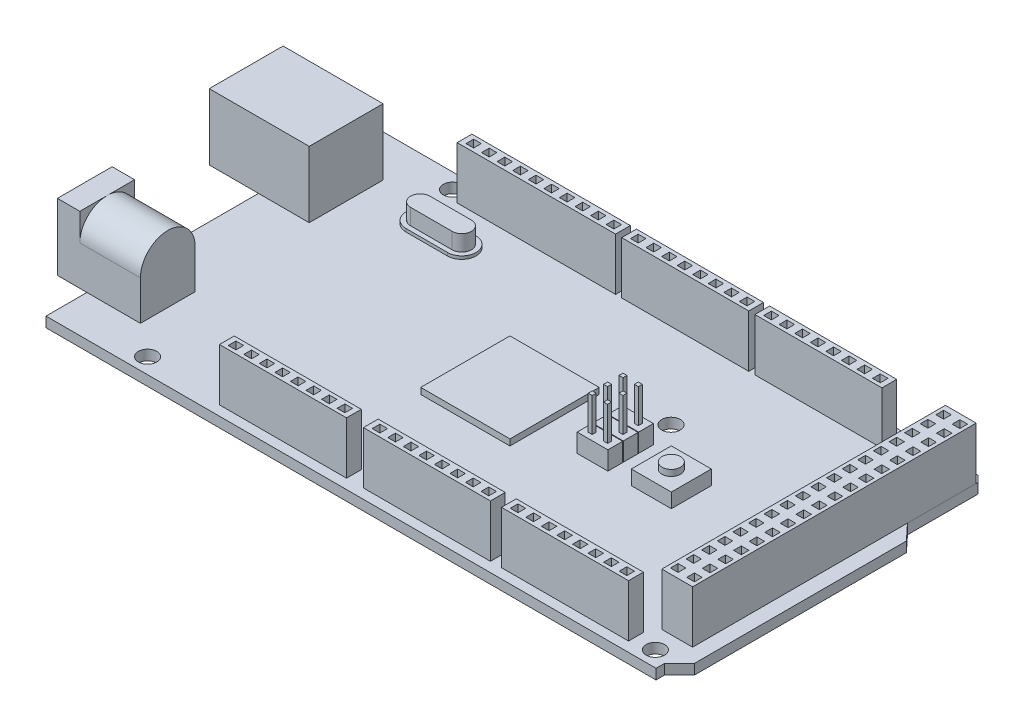
SolidWorks part; units mm, degrees
ref_plane "Front Plane" through (0, 0, 0) normal (0, 0, 1) x (1, 0, 0)
ref_plane "Top Plane" through (0, 0, 0) normal (0, 1, 0) x (1, 0, 0)
ref_plane "Right Plane" through (0, 0, 0) normal (1, 0, 0) x (0, 0, -1)
sketch "Sketch3" plane through (0, 0, 0) normal (0, 1, 0) x (1, 0, 0)
  line L0 (35.6106, 186.2409) -> (435.6106, 186.2409) construction
  line L1 (50.8, -26.67) -> (-50.8, -26.67)
  line L2 (50.8, -26.67) -> (50.8, 26.67)
  line L3 (50.8, 26.67) -> (-50.8, 26.67)
  line L4 (-50.8, -26.67) -> (-50.8, 26.67)
  line L5 (0, 26.67) -> (0, -26.67) construction
  line L6 (50.8, 0) -> (-50.8, 0) construction
  line L7 (47.3673, 26.67) -> (48.3673, 25.67)
  line L8 (48.3673, 25.67) -> (48.3673, 14.2013)
  line L9 (48.3673, 14.2013) -> (50.8, 11.5986)
  line L10 (50.8, -22.8744) -> (48.3673, -25.3071)
  line L11 (48.3673, -25.3071) -> (48.3673, -26.67)
  circle A0 centre (-36.83, -24.13) radius 1.5
  circle A1 centre (-35.56, 24.17) radius 1.5
  circle A2 centre (39.37, 24.17) radius 1.5
  circle A3 centre (45.72, -24.13) radius 1.5
  circle A4 centre (15.24, -19.05) radius 1.5
  circle A5 centre (15.3, 8.83) radius 1.5
  point P0 (0, 0)
  dimension "D4" = 3
  dimension "D7" = 3
  dimension "D1" = 101.6
  dimension "D2" = 53.34
  dimension "D3" = 15.24
  dimension "D5" = 2.5
  dimension "D6" = 2.54
  dimension "D8" = 13.97
  dimension "D9" = 90.17
  dimension "D10" = 96.52
  dimension "D11" = 66.04
  dimension "D12" = 7.62
  dimension "D13" = 1
  dimension "D14" = 1
  dimension "D15" = 35.5
  dimension "D16" = 35.5
extrude "Boss-Extrude1" add sketch "Sketch3" along normal blind 1.65 contours L11 L10 L2 L9 L8 L7 L3 L4 L1 A4 A3 A2 A1 A0
sketch "Sketch4" plane through (0, 1.65, 0) normal (0, 1, 0) x (1, 0, 0)
  line L0 (-50.8, -26.67) -> (-50.8, 26.67) construction
  line L1 (-42.55, 19.87) -> (-58.8, 19.87)
  line L2 (-42.55, 19.87) -> (-42.55, 7.87)
  line L3 (-42.55, 7.87) -> (-58.8, 7.87)
  line L4 (-58.8, 19.87) -> (-58.8, 7.87)
  line L5 (-50.675, 7.87) -> (-50.675, 19.87) construction
  line L6 (-42.55, 13.87) -> (-58.8, 13.87) construction
  line L13 (47.3673, 26.67) -> (-50.8, 26.67) construction
  point P60 (-50.675, 13.87)
  dimension "D1" = 16.25
  dimension "D2" = 12
  dimension "D3" = 8
  dimension "D4" = 6.8
extrude "Boss-Extrude2" add sketch "Sketch4" along normal blind 10.75 separate body
sketch "Sketch5" plane through (0, 1.65, 0) normal (0, 1, 0) x (1, 0, 0)
  line L0 (-50.8, -26.67) -> (-50.8, 26.67) construction
  line L1 (-42.1, -11.12) -> (-55.6, -11.12)
  line L2 (-42.1, -11.12) -> (-42.1, -20.02)
  line L3 (-42.1, -20.02) -> (-55.6, -20.02)
  line L4 (-55.6, -11.12) -> (-55.6, -20.02)
  line L5 (-48.85, -20.02) -> (-48.85, -11.12) construction
  line L6 (-42.1, -15.57) -> (-55.6, -15.57) construction
  line L7 (48.3673, -26.67) -> (-50.8, -26.67) construction
  point P64 (-48.85, -15.57)
  dimension "D1" = 13.5
  dimension "D2" = 8.9
  dimension "D3" = 4.8
  dimension "D4" = 6.65
extrude "Boss-Extrude3" add sketch "Sketch5" along normal blind 10.85 separate body
sketch "Sketch6" plane through (-42.1, 0, 0) normal (1, 0, 0) x (0, 0, -1)
  line L0 (-20.02, 12.5) -> (-20.02, 1.65) construction
  line L1 (-11.12, 12.5) -> (-11.12, 1.65) construction
  line L2 (-20.02, 12.5) -> (-11.12, 12.5) construction
  line L3 (-20.02, 8.05) -> (-20.02, 13.329)
  line L4 (-20.02, 13.329) -> (-11.12, 13.329)
  line L5 (-11.12, 13.329) -> (-11.12, 8.05)
  arc A0 (-20.02, 8.05) -> (-11.12, 8.05) centre (-15.57, 8.05) cw
extrude "Cut-Extrude1" cut sketch "Sketch6" against normal offset from surface (9.85 mm away) 3.65 up to face at (-55.6, 7.075, 15.57)
sketch "Sketch7" plane through (-58.8, 0, 0) normal (-1, 0, 0) x (0, 0, 1)
  line L0 (-7.87, 12.4) -> (-7.87, 1.65) construction
  line L1 (-18.22, 2.95) -> (-9.52, 2.95)
  line L2 (-18.22, 2.95) -> (-18.22, 9.1)
  line L3 (-16.22, 11.1) -> (-11.52, 11.1)
  line L4 (-9.52, 2.95) -> (-9.52, 9.1)
  line L5 (-13.87, 11.1) -> (-13.87, 2.95) construction
  line L6 (-18.22, 7.025) -> (-9.52, 7.025) construction
  line L7 (-19.87, 12.4) -> (-7.87, 12.4) construction
  line L8 (-18.22, 9.1) -> (-16.22, 11.1)
  line L9 (-11.02, 5.45) -> (-16.72, 5.45)
  line L10 (-11.02, 5.45) -> (-11.02, 8.6)
  line L11 (-11.02, 8.6) -> (-16.72, 8.6)
  line L12 (-16.72, 5.45) -> (-16.72, 8.6)
  line L13 (-13.87, 8.6) -> (-13.87, 5.45) construction
  line L14 (-11.02, 7.025) -> (-16.72, 7.025) construction
  line L15 (-11.52, 11.1) -> (-9.52, 9.1)
  point P0 (-13.87, 7.025)
  point P1 (-9.52, 11.1)
  point P3 (-18.22, 11.1)
  point P6 (-7.87, 7.025)
  point P9 (-13.87, 12.4)
  point P10 (-13.87, 7.025)
  dimension "D1" = 1.65
  dimension "D2" = 1.3
  dimension "D3" = 5.7
  dimension "D4" = 3.15
extrude "Cut-Extrude2" cut sketch "Sketch7" against normal blind 13
sketch "Sketch8" plane through (-55.6, 0, 0) normal (-1, 0, 0) x (0, 0, 1)
  circle A0 centre (15.57, 8.05) radius 3
  circle A1 centre (15.57, 8.05) radius 0.75
  dimension "D1" = 6
  dimension "D2" = 1.5
extrude "Cut-Extrude3" cut sketch "Sketch8" against normal blind 10
fillet "Fillet1" radius 0.75 1 edges at (-55.6, 8.05, 16.32)
sketch "Sketch9" plane through (0, 1.65, 0) normal (0, 1, 0) x (1, 0, 0)
  line L0 (48.3673, 25.67) -> (48.3673, 14.2013) construction
  line L1 (48.3673, 25.37) -> (43.3673, 25.37)
  line L2 (48.3673, 25.37) -> (48.3673, -20.73)
  line L3 (48.3673, -20.73) -> (43.3673, -20.73)
  line L4 (43.3673, 25.37) -> (43.3673, -20.73)
  line L5 (45.8673, -20.73) -> (45.8673, 25.37) construction
  line L6 (48.3673, 2.32) -> (43.3673, 2.32) construction
  line L7 (47.3673, 26.67) -> (-50.8, 26.67) construction
  line L8 (45.1673, -18.63) -> (43.9173, -18.63)
  line L9 (46.5673, -19.88) -> (47.8173, -19.88)
  line L10 (46.5673, -19.88) -> (46.5673, -18.63)
  line L11 (46.5673, -18.63) -> (47.8173, -18.63)
  line L12 (47.8173, -19.88) -> (47.8173, -18.63)
  line L13 (47.1923, -18.63) -> (47.1923, -19.88) construction
  line L14 (46.5673, -19.255) -> (47.8173, -19.255) construction
  line L15 (43.9173, -19.88) -> (43.9173, -18.63)
  line L16 (45.1673, -19.88) -> (43.9173, -19.88)
  line L17 (45.1673, -19.88) -> (45.1673, -18.63)
  line L18 (45.1673, -19.255) -> (43.9173, -19.255) construction
  line L19 (44.5423, -18.63) -> (44.5423, -19.88) construction
  line L20 (45.1673, -16.0918) -> (43.9173, -16.0918)
  line L21 (46.5673, -17.3418) -> (47.8173, -17.3418)
  line L22 (46.5673, -17.3418) -> (46.5673, -16.0918)
  line L23 (46.5673, -16.0918) -> (47.8173, -16.0918)
  line L24 (47.8173, -17.3418) -> (47.8173, -16.0918)
  line L25 (43.9173, -17.3418) -> (43.9173, -16.0918)
  line L26 (45.1673, -17.3418) -> (43.9173, -17.3418)
  line L27 (45.1673, -17.3418) -> (45.1673, -16.0918)
  line L28 (47.1923, -16.0918) -> (47.1923, -17.3418) construction
  line L29 (46.5673, -16.7168) -> (47.8173, -16.7168) construction
  line L30 (45.1673, -16.7168) -> (43.9173, -16.7168) construction
  line L31 (44.5423, -16.0918) -> (44.5423, -17.3418) construction
  line L32 (45.1673, -13.5535) -> (43.9173, -13.5535)
  line L33 (46.5673, -14.8035) -> (47.8173, -14.8035)
  line L34 (46.5673, -14.8035) -> (46.5673, -13.5535)
  line L35 (46.5673, -13.5535) -> (47.8173, -13.5535)
  line L36 (47.8173, -14.8035) -> (47.8173, -13.5535)
  line L37 (43.9173, -14.8035) -> (43.9173, -13.5535)
  line L38 (45.1673, -14.8035) -> (43.9173, -14.8035)
  line L39 (45.1673, -14.8035) -> (45.1673, -13.5535)
  line L40 (47.1923, -13.5535) -> (47.1923, -14.8035) construction
  line L41 (46.5673, -14.1785) -> (47.8173, -14.1785) construction
  line L42 (45.1673, -14.1785) -> (43.9173, -14.1785) construction
  line L43 (44.5423, -13.5535) -> (44.5423, -14.8035) construction
  line L44 (45.1673, -11.0153) -> (43.9173, -11.0153)
  line L45 (46.5673, -12.2653) -> (47.8173, -12.2653)
  line L46 (46.5673, -12.2653) -> (46.5673, -11.0153)
  line L47 (46.5673, -11.0153) -> (47.8173, -11.0153)
  line L48 (47.8173, -12.2653) -> (47.8173, -11.0153)
  line L49 (43.9173, -12.2653) -> (43.9173, -11.0153)
  line L50 (45.1673, -12.2653) -> (43.9173, -12.2653)
  line L51 (45.1673, -12.2653) -> (45.1673, -11.0153)
  line L52 (47.1923, -11.0153) -> (47.1923, -12.2653) construction
  line L53 (46.5673, -11.6403) -> (47.8173, -11.6403) construction
  line L54 (45.1673, -11.6403) -> (43.9173, -11.6403) construction
  line L55 (44.5423, -11.0153) -> (44.5423, -12.2653) construction
  line L56 (45.1673, -8.4771) -> (43.9173, -8.4771)
  line L57 (46.5673, -9.7271) -> (47.8173, -9.7271)
  line L58 (46.5673, -9.7271) -> (46.5673, -8.4771)
  line L59 (46.5673, -8.4771) -> (47.8173, -8.4771)
  line L60 (47.8173, -9.7271) -> (47.8173, -8.4771)
  line L61 (43.9173, -9.7271) -> (43.9173, -8.4771)
  line L62 (45.1673, -9.7271) -> (43.9173, -9.7271)
  line L63 (45.1673, -9.7271) -> (45.1673, -8.4771)
  line L64 (47.1923, -8.4771) -> (47.1923, -9.7271) construction
  line L65 (46.5673, -9.1021) -> (47.8173, -9.1021) construction
  line L66 (45.1673, -9.1021) -> (43.9173, -9.1021) construction
  line L67 (44.5423, -8.4771) -> (44.5423, -9.7271) construction
  line L68 (45.1673, -5.9388) -> (43.9173, -5.9388)
  line L69 (46.5673, -7.1888) -> (47.8173, -7.1888)
  line L70 (46.5673, -7.1888) -> (46.5673, -5.9388)
  line L71 (46.5673, -5.9388) -> (47.8173, -5.9388)
  line L72 (47.8173, -7.1888) -> (47.8173, -5.9388)
  line L73 (43.9173, -7.1888) -> (43.9173, -5.9388)
  line L74 (45.1673, -7.1888) -> (43.9173, -7.1888)
  line L75 (45.1673, -7.1888) -> (45.1673, -5.9388)
  line L76 (47.1923, -5.9388) -> (47.1923, -7.1888) construction
  line L77 (46.5673, -6.5638) -> (47.8173, -6.5638) construction
  line L78 (45.1673, -6.5638) -> (43.9173, -6.5638) construction
  line L79 (44.5423, -5.9388) -> (44.5423, -7.1888) construction
  line L80 (45.1673, -3.4006) -> (43.9173, -3.4006)
  line L81 (46.5673, -4.6506) -> (47.8173, -4.6506)
  line L82 (46.5673, -4.6506) -> (46.5673, -3.4006)
  line L83 (46.5673, -3.4006) -> (47.8173, -3.4006)
  line L84 (47.8173, -4.6506) -> (47.8173, -3.4006)
  line L85 (43.9173, -4.6506) -> (43.9173, -3.4006)
  line L86 (45.1673, -4.6506) -> (43.9173, -4.6506)
  line L87 (45.1673, -4.6506) -> (45.1673, -3.4006)
  line L88 (47.1923, -3.4006) -> (47.1923, -4.6506) construction
  line L89 (46.5673, -4.0256) -> (47.8173, -4.0256) construction
  line L90 (45.1673, -4.0256) -> (43.9173, -4.0256) construction
  line L91 (44.5423, -3.4006) -> (44.5423, -4.6506) construction
  line L92 (45.1673, -0.8624) -> (43.9173, -0.8624)
  line L93 (46.5673, -2.1124) -> (47.8173, -2.1124)
  line L94 (46.5673, -2.1124) -> (46.5673, -0.8624)
  line L95 (46.5673, -0.8624) -> (47.8173, -0.8624)
  line L96 (47.8173, -2.1124) -> (47.8173, -0.8624)
  line L97 (43.9173, -2.1124) -> (43.9173, -0.8624)
  line L98 (45.1673, -2.1124) -> (43.9173, -2.1124)
  line L99 (45.1673, -2.1124) -> (45.1673, -0.8624)
  line L100 (47.1923, -0.8624) -> (47.1923, -2.1124) construction
  line L101 (46.5673, -1.4874) -> (47.8173, -1.4874) construction
  line L102 (45.1673, -1.4874) -> (43.9173, -1.4874) construction
  line L103 (44.5423, -0.8624) -> (44.5423, -2.1124) construction
  line L104 (45.1673, 1.6759) -> (43.9173, 1.6759)
  line L105 (46.5673, 0.4259) -> (47.8173, 0.4259)
  line L106 (46.5673, 0.4259) -> (46.5673, 1.6759)
  line L107 (46.5673, 1.6759) -> (47.8173, 1.6759)
  line L108 (47.8173, 0.4259) -> (47.8173, 1.6759)
  line L109 (43.9173, 0.4259) -> (43.9173, 1.6759)
  line L110 (45.1673, 0.4259) -> (43.9173, 0.4259)
  line L111 (45.1673, 0.4259) -> (45.1673, 1.6759)
  line L112 (47.1923, 1.6759) -> (47.1923, 0.4259) construction
  line L113 (46.5673, 1.0509) -> (47.8173, 1.0509) construction
  line L114 (45.1673, 1.0509) -> (43.9173, 1.0509) construction
  line L115 (44.5423, 1.6759) -> (44.5423, 0.4259) construction
  line L116 (45.1673, 4.2141) -> (43.9173, 4.2141)
  line L117 (46.5673, 2.9641) -> (47.8173, 2.9641)
  line L118 (46.5673, 2.9641) -> (46.5673, 4.2141)
  line L119 (46.5673, 4.2141) -> (47.8173, 4.2141)
  line L120 (47.8173, 2.9641) -> (47.8173, 4.2141)
  line L121 (43.9173, 2.9641) -> (43.9173, 4.2141)
  line L122 (45.1673, 2.9641) -> (43.9173, 2.9641)
  line L123 (45.1673, 2.9641) -> (45.1673, 4.2141)
  line L124 (47.1923, 4.2141) -> (47.1923, 2.9641) construction
  line L125 (46.5673, 3.5891) -> (47.8173, 3.5891) construction
  line L126 (45.1673, 3.5891) -> (43.9173, 3.5891) construction
  line L127 (44.5423, 4.2141) -> (44.5423, 2.9641) construction
  line L128 (45.1673, 6.7524) -> (43.9173, 6.7524)
  line L129 (46.5673, 5.5024) -> (47.8173, 5.5024)
  line L130 (46.5673, 5.5024) -> (46.5673, 6.7524)
  line L131 (46.5673, 6.7524) -> (47.8173, 6.7524)
  line L132 (47.8173, 5.5024) -> (47.8173, 6.7524)
  line L133 (43.9173, 5.5024) -> (43.9173, 6.7524)
  line L134 (45.1673, 5.5024) -> (43.9173, 5.5024)
  line L135 (45.1673, 5.5024) -> (45.1673, 6.7524)
  line L136 (47.1923, 6.7524) -> (47.1923, 5.5024) construction
  line L137 (46.5673, 6.1274) -> (47.8173, 6.1274) construction
  line L138 (45.1673, 6.1274) -> (43.9173, 6.1274) construction
  line L139 (44.5423, 6.7524) -> (44.5423, 5.5024) construction
  line L140 (45.1673, 9.2906) -> (43.9173, 9.2906)
  line L141 (46.5673, 8.0406) -> (47.8173, 8.0406)
  line L142 (46.5673, 8.0406) -> (46.5673, 9.2906)
  line L143 (46.5673, 9.2906) -> (47.8173, 9.2906)
  line L144 (47.8173, 8.0406) -> (47.8173, 9.2906)
  line L145 (43.9173, 8.0406) -> (43.9173, 9.2906)
  line L146 (45.1673, 8.0406) -> (43.9173, 8.0406)
  line L147 (45.1673, 8.0406) -> (45.1673, 9.2906)
  line L148 (47.1923, 9.2906) -> (47.1923, 8.0406) construction
  line L149 (46.5673, 8.6656) -> (47.8173, 8.6656) construction
  line L150 (45.1673, 8.6656) -> (43.9173, 8.6656) construction
  line L151 (44.5423, 9.2906) -> (44.5423, 8.0406) construction
  line L152 (45.1673, 11.8288) -> (43.9173, 11.8288)
  line L153 (46.5673, 10.5788) -> (47.8173, 10.5788)
  line L154 (46.5673, 10.5788) -> (46.5673, 11.8288)
  line L155 (46.5673, 11.8288) -> (47.8173, 11.8288)
  line L156 (47.8173, 10.5788) -> (47.8173, 11.8288)
  line L157 (43.9173, 10.5788) -> (43.9173, 11.8288)
  line L158 (45.1673, 10.5788) -> (43.9173, 10.5788)
  line L159 (45.1673, 10.5788) -> (45.1673, 11.8288)
  line L160 (47.1923, 11.8288) -> (47.1923, 10.5788) construction
  line L161 (46.5673, 11.2038) -> (47.8173, 11.2038) construction
  line L162 (45.1673, 11.2038) -> (43.9173, 11.2038) construction
  line L163 (44.5423, 11.8288) -> (44.5423, 10.5788) construction
  line L164 (45.1673, 14.3671) -> (43.9173, 14.3671)
  line L165 (46.5673, 13.1171) -> (47.8173, 13.1171)
  line L166 (46.5673, 13.1171) -> (46.5673, 14.3671)
  line L167 (46.5673, 14.3671) -> (47.8173, 14.3671)
  line L168 (47.8173, 13.1171) -> (47.8173, 14.3671)
  line L169 (43.9173, 13.1171) -> (43.9173, 14.3671)
  line L170 (45.1673, 13.1171) -> (43.9173, 13.1171)
  line L171 (45.1673, 13.1171) -> (45.1673, 14.3671)
  line L172 (47.1923, 14.3671) -> (47.1923, 13.1171) construction
  line L173 (46.5673, 13.7421) -> (47.8173, 13.7421) construction
  line L174 (45.1673, 13.7421) -> (43.9173, 13.7421) construction
  line L175 (44.5423, 14.3671) -> (44.5423, 13.1171) construction
  line L176 (45.1673, 16.9053) -> (43.9173, 16.9053)
  line L177 (46.5673, 15.6553) -> (47.8173, 15.6553)
  line L178 (46.5673, 15.6553) -> (46.5673, 16.9053)
  line L179 (46.5673, 16.9053) -> (47.8173, 16.9053)
  line L180 (47.8173, 15.6553) -> (47.8173, 16.9053)
  line L181 (43.9173, 15.6553) -> (43.9173, 16.9053)
  line L182 (45.1673, 15.6553) -> (43.9173, 15.6553)
  line L183 (45.1673, 15.6553) -> (45.1673, 16.9053)
  line L184 (47.1923, 16.9053) -> (47.1923, 15.6553) construction
  line L185 (46.5673, 16.2803) -> (47.8173, 16.2803) construction
  line L186 (45.1673, 16.2803) -> (43.9173, 16.2803) construction
  line L187 (44.5423, 16.9053) -> (44.5423, 15.6553) construction
  line L188 (45.1673, 19.4435) -> (43.9173, 19.4435)
  line L189 (46.5673, 18.1935) -> (47.8173, 18.1935)
  line L190 (46.5673, 18.1935) -> (46.5673, 19.4435)
  line L191 (46.5673, 19.4435) -> (47.8173, 19.4435)
  line L192 (47.8173, 18.1935) -> (47.8173, 19.4435)
  line L193 (43.9173, 18.1935) -> (43.9173, 19.4435)
  line L194 (45.1673, 18.1935) -> (43.9173, 18.1935)
  line L195 (45.1673, 18.1935) -> (45.1673, 19.4435)
  line L196 (47.1923, 19.4435) -> (47.1923, 18.1935) construction
  line L197 (46.5673, 18.8185) -> (47.8173, 18.8185) construction
  line L198 (45.1673, 18.8185) -> (43.9173, 18.8185) construction
  line L199 (44.5423, 19.4435) -> (44.5423, 18.1935) construction
  line L200 (45.1673, 21.9818) -> (43.9173, 21.9818)
  line L201 (46.5673, 20.7318) -> (47.8173, 20.7318)
  line L202 (46.5673, 20.7318) -> (46.5673, 21.9818)
  line L203 (46.5673, 21.9818) -> (47.8173, 21.9818)
  line L204 (47.8173, 20.7318) -> (47.8173, 21.9818)
  line L205 (43.9173, 20.7318) -> (43.9173, 21.9818)
  line L206 (45.1673, 20.7318) -> (43.9173, 20.7318)
  line L207 (45.1673, 20.7318) -> (45.1673, 21.9818)
  line L208 (47.1923, 21.9818) -> (47.1923, 20.7318) construction
  line L209 (46.5673, 21.3568) -> (47.8173, 21.3568) construction
  line L210 (45.1673, 21.3568) -> (43.9173, 21.3568) construction
  line L211 (44.5423, 21.9818) -> (44.5423, 20.7318) construction
  line L212 (45.1673, 24.52) -> (43.9173, 24.52)
  line L213 (46.5673, 23.27) -> (47.8173, 23.27)
  line L214 (46.5673, 23.27) -> (46.5673, 24.52)
  line L215 (46.5673, 24.52) -> (47.8173, 24.52)
  line L216 (47.8173, 23.27) -> (47.8173, 24.52)
  line L217 (43.9173, 23.27) -> (43.9173, 24.52)
  line L218 (45.1673, 23.27) -> (43.9173, 23.27)
  line L219 (45.1673, 23.27) -> (45.1673, 24.52)
  line L220 (47.1923, 24.52) -> (47.1923, 23.27) construction
  line L221 (46.5673, 23.895) -> (47.8173, 23.895) construction
  line L222 (45.1673, 23.895) -> (43.9173, 23.895) construction
  line L223 (44.5423, 24.52) -> (44.5423, 23.27) construction
  point P8 (47.1923, -19.255)
  point P16 (44.5423, -19.255)
  point P22 (47.1923, -16.7168)
  point P30 (44.5423, -16.7168)
  point P40 (47.1923, -14.1785)
  point P48 (44.5423, -14.1785)
  point P58 (47.1923, -11.6403)
  point P66 (44.5423, -11.6403)
  point P81 (47.1923, -9.1021)
  point P89 (44.5423, -9.1021)
  point P96 (45.8673, 2.32)
  point P104 (47.1923, -6.5638)
  point P112 (44.5423, -6.5638)
  point P122 (47.1923, -4.0256)
  point P130 (44.5423, -4.0256)
  point P140 (47.1923, -1.4874)
  point P148 (44.5423, -1.4874)
  point P158 (47.1923, 1.0509)
  point P166 (44.5423, 1.0509)
  point P176 (47.1923, 3.5891)
  point P184 (44.5423, 3.5891)
  point P194 (47.1923, 6.1274)
  point P202 (44.5423, 6.1274)
  point P212 (47.1923, 8.6656)
  point P220 (44.5423, 8.6656)
  point P230 (47.1923, 11.2038)
  point P238 (44.5423, 11.2038)
  point P248 (47.1923, 13.7421)
  point P256 (44.5423, 13.7421)
  point P266 (47.1923, 16.2803)
  point P274 (44.5423, 16.2803)
  point P284 (47.1923, 18.8185)
  point P292 (44.5423, 18.8185)
  point P302 (47.1923, 21.3568)
  point P310 (44.5423, 21.3568)
  point P320 (47.1923, 23.895)
  point P328 (44.5423, 23.895)
  dimension "D1" = 46.1
  dimension "D2" = 5
  dimension "D3" = 1.3
  dimension "D4" = 1.25
  dimension "D5" = 0.85
  dimension "D6" = 1.4
  dimension "D8" = 0.85
  dimension "D7" = 18
extrude "Boss-Extrude4" add sketch "Sketch9" along normal blind 8.5 separate body
sketch "Sketch10" plane through (0, 1.65, 0) normal (0, 1, 0) x (1, 0, 0)
  line L0 (-50.8, -26.67) -> (-50.8, 26.67) construction
  line L1 (-33.3, 25.07) -> (-7.55, 25.07)
  line L2 (-33.3, 25.07) -> (-33.3, 22.67)
  line L3 (-33.3, 22.67) -> (-7.55, 22.67)
  line L4 (-7.55, 25.07) -> (-7.55, 22.67)
  line L5 (-20.425, 22.67) -> (-20.425, 25.07) construction
  line L6 (-33.3, 23.87) -> (-7.55, 23.87) construction
  line L7 (-6.55, 25.07) -> (14.1, 25.07)
  line L8 (-6.55, 25.07) -> (-6.55, 22.67)
  line L9 (-6.55, 22.67) -> (14.1, 22.67)
  line L10 (14.1, 25.07) -> (14.1, 22.67)
  line L11 (3.775, 22.67) -> (3.775, 25.07) construction
  line L12 (-6.55, 23.87) -> (14.1, 23.87) construction
  line L13 (15.1, 25.07) -> (35.75, 25.07)
  line L14 (15.1, 25.07) -> (15.1, 22.67)
  line L15 (15.1, 22.67) -> (35.75, 22.67)
  line L16 (35.75, 25.07) -> (35.75, 22.67)
  line L17 (25.425, 22.67) -> (25.425, 25.07) construction
  line L18 (15.1, 23.87) -> (35.75, 23.87) construction
  line L19 (47.3673, 26.67) -> (-50.8, 26.67) construction
  line L20 (42.3, -22.67) -> (21.65, -22.67)
  line L21 (42.3, -22.67) -> (42.3, -25.07)
  line L22 (42.3, -25.07) -> (21.65, -25.07)
  line L23 (21.65, -22.67) -> (21.65, -25.07)
  line L24 (31.975, -25.07) -> (31.975, -22.67) construction
  line L25 (42.3, -23.87) -> (21.65, -23.87) construction
  line L26 (19.85, -22.67) -> (-0.8, -22.67)
  line L27 (19.85, -22.67) -> (19.85, -25.07)
  line L28 (19.85, -25.07) -> (-0.8, -25.07)
  line L29 (-0.8, -22.67) -> (-0.8, -25.07)
  line L30 (9.525, -25.07) -> (9.525, -22.67) construction
  line L31 (19.85, -23.87) -> (-0.8, -23.87) construction
  line L32 (-3.55, -22.67) -> (-24.2, -22.67)
  line L33 (-3.55, -22.67) -> (-3.55, -25.07)
  line L34 (-3.55, -25.07) -> (-24.2, -25.07)
  line L35 (-24.2, -22.67) -> (-24.2, -25.07)
  line L36 (-13.875, -25.07) -> (-13.875, -22.67) construction
  line L37 (-3.55, -23.87) -> (-24.2, -23.87) construction
  line L38 (48.3673, -26.67) -> (-50.8, -26.67) construction
  line L39 (9.4714, 23.245) -> (10.7214, 23.245)
  line L40 (50.8, -22.8744) -> (50.8, 11.5986) construction
  line L41 (37.6714, -24.495) -> (38.9214, -24.495)
  line L42 (40.2, -24.495) -> (41.45, -24.495)
  line L43 (40.2, -24.495) -> (40.2, -23.245)
  line L44 (40.2, -23.245) -> (41.45, -23.245)
  line L45 (41.45, -24.495) -> (41.45, -23.245)
  line L46 (40.825, -23.245) -> (40.825, -24.495) construction
  line L47 (40.2, -23.87) -> (41.45, -23.87) construction
  line L48 (37.6714, -24.495) -> (37.6714, -23.245)
  line L49 (37.6714, -23.245) -> (38.9214, -23.245)
  line L50 (38.9214, -24.495) -> (38.9214, -23.245)
  line L51 (38.2964, -23.245) -> (38.2964, -24.495) construction
  line L52 (37.6714, -23.87) -> (38.9214, -23.87) construction
  line L53 (35.1429, -24.495) -> (36.3929, -24.495)
  line L54 (35.1429, -24.495) -> (35.1429, -23.245)
  line L55 (35.1429, -23.245) -> (36.3929, -23.245)
  line L56 (36.3929, -24.495) -> (36.3929, -23.245)
  line L57 (35.7679, -23.245) -> (35.7679, -24.495) construction
  line L58 (35.1429, -23.87) -> (36.3929, -23.87) construction
  line L59 (32.6143, -24.495) -> (33.8643, -24.495)
  line L60 (32.6143, -24.495) -> (32.6143, -23.245)
  line L61 (32.6143, -23.245) -> (33.8643, -23.245)
  line L62 (33.8643, -24.495) -> (33.8643, -23.245)
  line L63 (33.2393, -23.245) -> (33.2393, -24.495) construction
  line L64 (32.6143, -23.87) -> (33.8643, -23.87) construction
  line L65 (30.0857, -24.495) -> (31.3357, -24.495)
  line L66 (30.0857, -24.495) -> (30.0857, -23.245)
  line L67 (30.0857, -23.245) -> (31.3357, -23.245)
  line L68 (31.3357, -24.495) -> (31.3357, -23.245)
  line L69 (30.7107, -23.245) -> (30.7107, -24.495) construction
  line L70 (30.0857, -23.87) -> (31.3357, -23.87) construction
  line L71 (27.5571, -24.495) -> (28.8071, -24.495)
  line L72 (27.5571, -24.495) -> (27.5571, -23.245)
  line L73 (27.5571, -23.245) -> (28.8071, -23.245)
  line L74 (28.8071, -24.495) -> (28.8071, -23.245)
  line L75 (28.1821, -23.245) -> (28.1821, -24.495) construction
  line L76 (27.5571, -23.87) -> (28.8071, -23.87) construction
  line L77 (25.0286, -24.495) -> (26.2786, -24.495)
  line L78 (25.0286, -24.495) -> (25.0286, -23.245)
  line L79 (25.0286, -23.245) -> (26.2786, -23.245)
  line L80 (26.2786, -24.495) -> (26.2786, -23.245)
  line L81 (25.6536, -23.245) -> (25.6536, -24.495) construction
  line L82 (25.0286, -23.87) -> (26.2786, -23.87) construction
  line L83 (22.5, -24.495) -> (23.75, -24.495)
  line L84 (22.5, -24.495) -> (22.5, -23.245)
  line L85 (22.5, -23.245) -> (23.75, -23.245)
  line L86 (23.75, -24.495) -> (23.75, -23.245)
  line L87 (23.125, -23.245) -> (23.125, -24.495) construction
  line L88 (22.5, -23.87) -> (23.75, -23.87) construction
  line L89 (21.65, -23.87) -> (19.85, -23.87) construction
  line L90 (20.75, -23.87) -> (20.75, -21.6877) construction
  line L91 (-0.8, -23.87) -> (-3.55, -23.87) construction
  line L92 (-2.175, -23.87) -> (-2.175, -21.9894) construction
  line L93 (19, -23.87) -> (17.75, -23.87) construction
  line L94 (18.375, -23.245) -> (18.375, -24.495) construction
  line L95 (16.4714, -23.87) -> (15.2214, -23.87) construction
  line L96 (15.8464, -23.245) -> (15.8464, -24.495) construction
  line L97 (13.9429, -23.87) -> (12.6929, -23.87) construction
  line L98 (13.3179, -23.245) -> (13.3179, -24.495) construction
  line L99 (11.4143, -23.87) -> (10.1643, -23.87) construction
  line L100 (10.7893, -23.245) -> (10.7893, -24.495) construction
  line L101 (8.8857, -23.87) -> (7.6357, -23.87) construction
  line L102 (8.2607, -23.245) -> (8.2607, -24.495) construction
  line L103 (6.3571, -23.87) -> (5.1071, -23.87) construction
  line L104 (5.7321, -23.245) -> (5.7321, -24.495) construction
  line L105 (3.8286, -23.87) -> (2.5786, -23.87) construction
  line L106 (3.2036, -23.245) -> (3.2036, -24.495) construction
  line L107 (1.3, -23.87) -> (0.05, -23.87) construction
  line L108 (0.675, -23.245) -> (0.675, -24.495) construction
  line L109 (17.75, -24.495) -> (17.75, -23.245)
  line L110 (19, -23.245) -> (17.75, -23.245)
  line L111 (19, -24.495) -> (19, -23.245)
  line L112 (19, -24.495) -> (17.75, -24.495)
  line L113 (15.2214, -24.495) -> (15.2214, -23.245)
  line L114 (16.4714, -23.245) -> (15.2214, -23.245)
  line L115 (16.4714, -24.495) -> (16.4714, -23.245)
  line L116 (16.4714, -24.495) -> (15.2214, -24.495)
  line L117 (12.6929, -24.495) -> (12.6929, -23.245)
  line L118 (13.9429, -23.245) -> (12.6929, -23.245)
  line L119 (13.9429, -24.495) -> (13.9429, -23.245)
  line L120 (13.9429, -24.495) -> (12.6929, -24.495)
  line L121 (10.1643, -24.495) -> (10.1643, -23.245)
  line L122 (11.4143, -23.245) -> (10.1643, -23.245)
  line L123 (11.4143, -24.495) -> (11.4143, -23.245)
  line L124 (11.4143, -24.495) -> (10.1643, -24.495)
  line L125 (7.6357, -24.495) -> (7.6357, -23.245)
  line L126 (8.8857, -23.245) -> (7.6357, -23.245)
  line L127 (8.8857, -24.495) -> (8.8857, -23.245)
  line L128 (8.8857, -24.495) -> (7.6357, -24.495)
  line L129 (5.1071, -24.495) -> (5.1071, -23.245)
  line L130 (6.3571, -23.245) -> (5.1071, -23.245)
  line L131 (6.3571, -24.495) -> (6.3571, -23.245)
  line L132 (6.3571, -24.495) -> (5.1071, -24.495)
  line L133 (2.5786, -24.495) -> (2.5786, -23.245)
  line L134 (3.8286, -23.245) -> (2.5786, -23.245)
  line L135 (3.8286, -24.495) -> (3.8286, -23.245)
  line L136 (0.05, -24.495) -> (0.05, -23.245)
  line L137 (1.3, -23.245) -> (0.05, -23.245)
  line L138 (1.3, -24.495) -> (1.3, -23.245)
  line L139 (1.3, -24.495) -> (0.05, -24.495)
  line L140 (3.8286, -24.495) -> (2.5786, -24.495)
  line L141 (-5.025, -23.245) -> (-5.025, -24.495) construction
  line L142 (-5.65, -23.87) -> (-4.4, -23.87) construction
  line L143 (-7.5536, -23.245) -> (-7.5536, -24.495) construction
  line L144 (-8.1786, -23.87) -> (-6.9286, -23.87) construction
  line L145 (-10.0821, -23.245) -> (-10.0821, -24.495) construction
  line L146 (-10.7071, -23.87) -> (-9.4571, -23.87) construction
  line L147 (-12.6107, -23.245) -> (-12.6107, -24.495) construction
  line L148 (-13.2357, -23.87) -> (-11.9857, -23.87) construction
  line L149 (-15.1393, -23.245) -> (-15.1393, -24.495) construction
  line L150 (-15.7643, -23.87) -> (-14.5143, -23.87) construction
  line L151 (-17.6679, -23.245) -> (-17.6679, -24.495) construction
  line L152 (-18.2929, -23.87) -> (-17.0429, -23.87) construction
  line L153 (-20.1964, -23.245) -> (-20.1964, -24.495) construction
  line L154 (-20.8214, -23.87) -> (-19.5714, -23.87) construction
  line L155 (-22.725, -23.245) -> (-22.725, -24.495) construction
  line L156 (-23.35, -23.87) -> (-22.1, -23.87) construction
  line L157 (-8.1786, -24.495) -> (-6.9286, -24.495)
  line L158 (-5.65, -24.495) -> (-4.4, -24.495)
  line L159 (-5.65, -24.495) -> (-5.65, -23.245)
  line L160 (-5.65, -23.245) -> (-4.4, -23.245)
  line L161 (-4.4, -24.495) -> (-4.4, -23.245)
  line L162 (-8.1786, -24.495) -> (-8.1786, -23.245)
  line L163 (-8.1786, -23.245) -> (-6.9286, -23.245)
  line L164 (-6.9286, -24.495) -> (-6.9286, -23.245)
  line L165 (-10.7071, -24.495) -> (-9.4571, -24.495)
  line L166 (-10.7071, -24.495) -> (-10.7071, -23.245)
  line L167 (-10.7071, -23.245) -> (-9.4571, -23.245)
  line L168 (-9.4571, -24.495) -> (-9.4571, -23.245)
  line L169 (-13.2357, -24.495) -> (-11.9857, -24.495)
  line L170 (-13.2357, -24.495) -> (-13.2357, -23.245)
  line L171 (-13.2357, -23.245) -> (-11.9857, -23.245)
  line L172 (-11.9857, -24.495) -> (-11.9857, -23.245)
  line L173 (-15.7643, -24.495) -> (-14.5143, -24.495)
  line L174 (-15.7643, -24.495) -> (-15.7643, -23.245)
  line L175 (-15.7643, -23.245) -> (-14.5143, -23.245)
  line L176 (-14.5143, -24.495) -> (-14.5143, -23.245)
  line L177 (-18.2929, -24.495) -> (-17.0429, -24.495)
  line L178 (-18.2929, -24.495) -> (-18.2929, -23.245)
  line L179 (-18.2929, -23.245) -> (-17.0429, -23.245)
  line L180 (-17.0429, -24.495) -> (-17.0429, -23.245)
  line L181 (-20.8214, -24.495) -> (-19.5714, -24.495)
  line L182 (-20.8214, -24.495) -> (-20.8214, -23.245)
  line L183 (-20.8214, -23.245) -> (-19.5714, -23.245)
  line L184 (-19.5714, -24.495) -> (-19.5714, -23.245)
  line L185 (-23.35, -24.495) -> (-22.1, -24.495)
  line L186 (-23.35, -24.495) -> (-23.35, -23.245)
  line L187 (-23.35, -23.245) -> (-22.1, -23.245)
  line L188 (-22.1, -24.495) -> (-22.1, -23.245)
  line L189 (31.1214, 23.245) -> (32.3714, 23.245)
  line L190 (33.65, 23.245) -> (34.9, 23.245)
  line L191 (33.65, 23.245) -> (33.65, 24.495)
  line L192 (33.65, 24.495) -> (34.9, 24.495)
  line L193 (34.9, 23.245) -> (34.9, 24.495)
  line L194 (34.275, 24.495) -> (34.275, 23.245) construction
  line L195 (33.65, 23.87) -> (34.9, 23.87) construction
  line L196 (31.1214, 23.245) -> (31.1214, 24.495)
  line L197 (31.1214, 24.495) -> (32.3714, 24.495)
  line L198 (32.3714, 23.245) -> (32.3714, 24.495)
  line L199 (31.7464, 24.495) -> (31.7464, 23.245) construction
  line L200 (31.1214, 23.87) -> (32.3714, 23.87) construction
  line L201 (28.5929, 23.245) -> (29.8429, 23.245)
  line L202 (28.5929, 23.245) -> (28.5929, 24.495)
  line L203 (28.5929, 24.495) -> (29.8429, 24.495)
  line L204 (29.8429, 23.245) -> (29.8429, 24.495)
  line L205 (29.2179, 24.495) -> (29.2179, 23.245) construction
  line L206 (28.5929, 23.87) -> (29.8429, 23.87) construction
  line L207 (26.0643, 23.245) -> (27.3143, 23.245)
  line L208 (26.0643, 23.245) -> (26.0643, 24.495)
  line L209 (26.0643, 24.495) -> (27.3143, 24.495)
  line L210 (27.3143, 23.245) -> (27.3143, 24.495)
  line L211 (26.6893, 24.495) -> (26.6893, 23.245) construction
  line L212 (26.0643, 23.87) -> (27.3143, 23.87) construction
  line L213 (23.5357, 23.245) -> (24.7857, 23.245)
  line L214 (23.5357, 23.245) -> (23.5357, 24.495)
  line L215 (23.5357, 24.495) -> (24.7857, 24.495)
  line L216 (24.7857, 23.245) -> (24.7857, 24.495)
  line L217 (24.1607, 24.495) -> (24.1607, 23.245) construction
  line L218 (23.5357, 23.87) -> (24.7857, 23.87) construction
  line L219 (21.0071, 23.245) -> (22.2571, 23.245)
  line L220 (21.0071, 23.245) -> (21.0071, 24.495)
  line L221 (21.0071, 24.495) -> (22.2571, 24.495)
  line L222 (22.2571, 23.245) -> (22.2571, 24.495)
  line L223 (21.6321, 24.495) -> (21.6321, 23.245) construction
  line L224 (21.0071, 23.87) -> (22.2571, 23.87) construction
  line L225 (18.4786, 23.245) -> (19.7286, 23.245)
  line L226 (18.4786, 23.245) -> (18.4786, 24.495)
  line L227 (18.4786, 24.495) -> (19.7286, 24.495)
  line L228 (19.7286, 23.245) -> (19.7286, 24.495)
  line L229 (19.1036, 24.495) -> (19.1036, 23.245) construction
  line L230 (18.4786, 23.87) -> (19.7286, 23.87) construction
  line L231 (15.95, 23.245) -> (17.2, 23.245)
  line L232 (15.95, 23.245) -> (15.95, 24.495)
  line L233 (15.95, 24.495) -> (17.2, 24.495)
  line L234 (17.2, 23.245) -> (17.2, 24.495)
  line L235 (16.575, 24.495) -> (16.575, 23.245) construction
  line L236 (15.95, 23.87) -> (17.2, 23.87) construction
  line L237 (15.1, 23.87) -> (14.1, 23.87) construction
  line L238 (14.6, 23.87) -> (14.6, 25.2515) construction
  line L239 (12, 23.245) -> (13.25, 23.245)
  line L240 (12, 23.245) -> (12, 24.495)
  line L241 (12, 24.495) -> (13.25, 24.495)
  line L242 (13.25, 23.245) -> (13.25, 24.495)
  line L243 (12.625, 24.495) -> (12.625, 23.245) construction
  line L244 (12, 23.87) -> (13.25, 23.87) construction
  line L245 (9.4714, 23.245) -> (9.4714, 24.495)
  line L246 (9.4714, 24.495) -> (10.7214, 24.495)
  line L247 (10.7214, 23.245) -> (10.7214, 24.495)
  line L248 (10.0964, 24.495) -> (10.0964, 23.245) construction
  line L249 (9.4714, 23.87) -> (10.7214, 23.87) construction
  line L250 (6.9429, 23.245) -> (8.1929, 23.245)
  line L251 (6.9429, 23.245) -> (6.9429, 24.495)
  line L252 (6.9429, 24.495) -> (8.1929, 24.495)
  line L253 (8.1929, 23.245) -> (8.1929, 24.495)
  line L254 (7.5679, 24.495) -> (7.5679, 23.245) construction
  line L255 (6.9429, 23.87) -> (8.1929, 23.87) construction
  line L256 (4.4143, 23.245) -> (5.6643, 23.245)
  line L257 (4.4143, 23.245) -> (4.4143, 24.495)
  line L258 (4.4143, 24.495) -> (5.6643, 24.495)
  line L259 (5.6643, 23.245) -> (5.6643, 24.495)
  line L260 (5.0393, 24.495) -> (5.0393, 23.245) construction
  line L261 (4.4143, 23.87) -> (5.6643, 23.87) construction
  line L262 (1.8857, 23.245) -> (3.1357, 23.245)
  line L263 (1.8857, 23.245) -> (1.8857, 24.495)
  line L264 (1.8857, 24.495) -> (3.1357, 24.495)
  line L265 (3.1357, 23.245) -> (3.1357, 24.495)
  line L266 (2.5107, 24.495) -> (2.5107, 23.245) construction
  line L267 (1.8857, 23.87) -> (3.1357, 23.87) construction
  line L268 (-0.6429, 23.245) -> (0.6071, 23.245)
  line L269 (-0.6429, 23.245) -> (-0.6429, 24.495)
  line L270 (-0.6429, 24.495) -> (0.6071, 24.495)
  line L271 (0.6071, 23.245) -> (0.6071, 24.495)
  line L272 (-0.0179, 24.495) -> (-0.0179, 23.245) construction
  line L273 (-0.6429, 23.87) -> (0.6071, 23.87) construction
  line L274 (-3.1714, 23.245) -> (-1.9214, 23.245)
  line L275 (-3.1714, 23.245) -> (-3.1714, 24.495)
  line L276 (-3.1714, 24.495) -> (-1.9214, 24.495)
  line L277 (-1.9214, 23.245) -> (-1.9214, 24.495)
  line L278 (-2.5464, 24.495) -> (-2.5464, 23.245) construction
  line L279 (-3.1714, 23.87) -> (-1.9214, 23.87) construction
  line L280 (-5.7, 23.245) -> (-4.45, 23.245)
  line L281 (-5.7, 23.245) -> (-5.7, 24.495)
  line L282 (-5.7, 24.495) -> (-4.45, 24.495)
  line L283 (-4.45, 23.245) -> (-4.45, 24.495)
  line L284 (-5.075, 24.495) -> (-5.075, 23.245) construction
  line L285 (-5.7, 23.87) -> (-4.45, 23.87) construction
  line L286 (-12.1833, 23.245) -> (-10.9333, 23.245)
  line L287 (-9.65, 23.245) -> (-8.4, 23.245)
  line L288 (-9.65, 23.245) -> (-9.65, 24.495)
  line L289 (-9.65, 24.495) -> (-8.4, 24.495)
  line L290 (-8.4, 23.245) -> (-8.4, 24.495)
  line L291 (-9.025, 24.495) -> (-9.025, 23.245) construction
  line L292 (-9.65, 23.87) -> (-8.4, 23.87) construction
  line L293 (-12.1833, 23.245) -> (-12.1833, 24.495)
  line L294 (-12.1833, 24.495) -> (-10.9333, 24.495)
  line L295 (-10.9333, 23.245) -> (-10.9333, 24.495)
  line L296 (-11.5583, 24.495) -> (-11.5583, 23.245) construction
  line L297 (-12.1833, 23.87) -> (-10.9333, 23.87) construction
  line L298 (-14.7167, 23.245) -> (-13.4667, 23.245)
  line L299 (-14.7167, 23.245) -> (-14.7167, 24.495)
  line L300 (-14.7167, 24.495) -> (-13.4667, 24.495)
  line L301 (-13.4667, 23.245) -> (-13.4667, 24.495)
  line L302 (-14.0917, 24.495) -> (-14.0917, 23.245) construction
  line L303 (-14.7167, 23.87) -> (-13.4667, 23.87) construction
  line L304 (-17.25, 23.245) -> (-16, 23.245)
  line L305 (-17.25, 23.245) -> (-17.25, 24.495)
  line L306 (-17.25, 24.495) -> (-16, 24.495)
  line L307 (-16, 23.245) -> (-16, 24.495)
  line L308 (-16.625, 24.495) -> (-16.625, 23.245) construction
  line L309 (-17.25, 23.87) -> (-16, 23.87) construction
  line L310 (-19.7833, 23.245) -> (-18.5333, 23.245)
  line L311 (-19.7833, 23.245) -> (-19.7833, 24.495)
  line L312 (-19.7833, 24.495) -> (-18.5333, 24.495)
  line L313 (-18.5333, 23.245) -> (-18.5333, 24.495)
  line L314 (-19.1583, 24.495) -> (-19.1583, 23.245) construction
  line L315 (-19.7833, 23.87) -> (-18.5333, 23.87) construction
  line L316 (-22.3167, 23.245) -> (-21.0667, 23.245)
  line L317 (-22.3167, 23.245) -> (-22.3167, 24.495)
  line L318 (-22.3167, 24.495) -> (-21.0667, 24.495)
  line L319 (-21.0667, 23.245) -> (-21.0667, 24.495)
  line L320 (-21.6917, 24.495) -> (-21.6917, 23.245) construction
  line L321 (-22.3167, 23.87) -> (-21.0667, 23.87) construction
  line L322 (-24.85, 23.245) -> (-23.6, 23.245)
  line L323 (-24.85, 23.245) -> (-24.85, 24.495)
  line L324 (-24.85, 24.495) -> (-23.6, 24.495)
  line L325 (-23.6, 23.245) -> (-23.6, 24.495)
  line L326 (-24.225, 24.495) -> (-24.225, 23.245) construction
  line L327 (-24.85, 23.87) -> (-23.6, 23.87) construction
  line L328 (-27.3833, 23.245) -> (-26.1333, 23.245)
  line L329 (-27.3833, 23.245) -> (-27.3833, 24.495)
  line L330 (-27.3833, 24.495) -> (-26.1333, 24.495)
  line L331 (-26.1333, 23.245) -> (-26.1333, 24.495)
  line L332 (-26.7583, 24.495) -> (-26.7583, 23.245) construction
  line L333 (-27.3833, 23.87) -> (-26.1333, 23.87) construction
  line L334 (-29.9167, 23.245) -> (-28.6667, 23.245)
  line L335 (-29.9167, 23.245) -> (-29.9167, 24.495)
  line L336 (-29.9167, 24.495) -> (-28.6667, 24.495)
  line L337 (-28.6667, 23.245) -> (-28.6667, 24.495)
  line L338 (-29.2917, 24.495) -> (-29.2917, 23.245) construction
  line L339 (-29.9167, 23.87) -> (-28.6667, 23.87) construction
  line L340 (-32.45, 23.245) -> (-31.2, 23.245)
  line L341 (-32.45, 23.245) -> (-32.45, 24.495)
  line L342 (-32.45, 24.495) -> (-31.2, 24.495)
  line L343 (-31.2, 23.245) -> (-31.2, 24.495)
  line L344 (-31.825, 24.495) -> (-31.825, 23.245) construction
  line L345 (-32.45, 23.87) -> (-31.2, 23.87) construction
  point P32 (40.825, -23.87)
  point P37 (38.2964, -23.87)
  point P46 (35.7679, -23.87)
  point P55 (33.2393, -23.87)
  point P60 (3.775, 23.87)
  point P72 (-20.425, 23.87)
  point P78 (25.425, 23.87)
  point P79 (30.7107, -23.87)
  point P85 (-13.875, -23.87)
  point P93 (9.525, -23.87)
  point P103 (28.1821, -23.87)
  point P109 (31.975, -23.87)
  point P117 (25.6536, -23.87)
  point P126 (23.125, -23.87)
  point P202 (18.375, -23.87)
  point P203 (15.8464, -23.87)
  point P204 (13.3179, -23.87)
  point P205 (10.7893, -23.87)
  point P206 (8.2607, -23.87)
  point P207 (5.7321, -23.87)
  point P208 (3.2036, -23.87)
  point P209 (0.675, -23.87)
  point P274 (-5.025, -23.87)
  point P275 (-7.5536, -23.87)
  point P276 (-10.0821, -23.87)
  point P277 (-12.6107, -23.87)
  point P278 (-15.1393, -23.87)
  point P279 (-17.6679, -23.87)
  point P280 (-20.1964, -23.87)
  point P281 (-22.725, -23.87)
  point P282 (34.275, 23.87)
  point P287 (31.7464, 23.87)
  point P296 (29.2179, 23.87)
  point P310 (26.6893, 23.87)
  point P319 (24.1607, 23.87)
  point P328 (21.6321, 23.87)
  point P337 (19.1036, 23.87)
  point P346 (16.575, 23.87)
  point P356 (12.625, 23.87)
  point P360 (-9.025, 23.87)
  point P361 (10.0964, 23.87)
  point P370 (7.5679, 23.87)
  point P384 (5.0393, 23.87)
  point P393 (2.5107, 23.87)
  point P402 (-0.0179, 23.87)
  point P411 (-2.5464, 23.87)
  point P420 (-5.075, 23.87)
  point P433 (-11.5583, 23.87)
  point P442 (-14.0917, 23.87)
  point P451 (-16.625, 23.87)
  point P465 (-19.1583, 23.87)
  point P474 (-21.6917, 23.87)
  point P483 (-24.225, 23.87)
  point P492 (-26.7583, 23.87)
  point P501 (-29.2917, 23.87)
  point P510 (-31.825, 23.87)
  dimension "D1" = 25.75
  dimension "D2" = 2.4
  dimension "D3" = 20.65
  dimension "D4" = 1
  dimension "D5" = 1
  dimension "D6" = 20.65
  dimension "D7" = 17.5
  dimension "D8" = 1.6
  dimension "D9" = 1.6
  dimension "D10" = 2.4
  dimension "D11" = 26.6
  dimension "D12" = 20.65
  dimension "D13" = 8.5
  dimension "D14" = 1.8
  dimension "D15" = 1.25
  dimension "D16" = 0.85
  dimension "D18" = 0.85
  dimension "D19" = 0.85
  dimension "D20" = 1.25
  dimension "D22" = 0.85
  dimension "D23" = 0.85
  dimension "D25" = 0.85
  dimension "D26" = 0.85
  dimension "D28" = 0.85
  dimension "D17" = 8
  dimension "D21" = 8
  dimension "D24" = 8
  dimension "D27" = 10
extrude "Boss-Extrude6" add sketch "Sketch10" along normal blind 8.5
sketch "Sketch11" plane through (0, 1.65, 0) normal (0, 1, 0) x (1, 0, 0)
  line L0 (-50.8, -26.67) -> (-50.8, 26.67) construction
  line L1 (-9.3, -7.25) -> (5.2, -7.25)
  line L2 (-9.3, -7.25) -> (-9.3, 7.25)
  line L3 (-9.3, 7.25) -> (5.2, 7.25)
  line L4 (5.2, -7.25) -> (5.2, 7.25)
  line L5 (-2.05, 7.25) -> (-2.05, -7.25) construction
  line L6 (-9.3, 0) -> (5.2, 0) construction
  point P0 (-2.05, 0)
  dimension "D1" = 14.5
  dimension "D2" = 56
extrude "Boss-Extrude7" add sketch "Sketch11" along normal blind 1
sketch "Sketch12" plane through (0, 1.65, 0) normal (0, 1, 0) x (1, 0, 0)
  line L0 (-33.375, 16.745) -> (-26.625, 16.745) construction
  line L1 (-33.375, 19.07) -> (-26.625, 19.07)
  line L2 (-33.375, 14.42) -> (-26.625, 14.42)
  line L3 (-50.8, -26.67) -> (-50.8, 26.67) construction
  line L4 (-33.3, 22.67) -> (-7.55, 22.67) construction
  arc A0 (-33.375, 19.07) -> (-33.375, 14.42) centre (-33.375, 16.745) ccw
  arc A1 (-26.625, 14.42) -> (-26.625, 19.07) centre (-26.625, 16.745) ccw
  point P2 (-30, 16.745)
  point P7 (-35.7, 16.745)
  point P8 (-24.3, 16.745)
  dimension "D1" = 11.4
  dimension "D2" = 4.65
  dimension "D3" = 26.5
  dimension "D4" = 3.6
extrude "Boss-Extrude8" add sketch "Sketch12" along normal blind 0.5
sketch "Sketch13" plane through (0, 2.15, 0) normal (0, 1, 0) x (1, 0, 0)
  line L0 (-33.375, 16.745) -> (-26.625, 16.745) construction
  line L1 (-33.375, 18.32) -> (-26.625, 18.32)
  line L2 (-33.375, 15.17) -> (-26.625, 15.17)
  arc A0 (-33.375, 18.32) -> (-33.375, 15.17) centre (-33.375, 16.745) ccw
  arc A1 (-26.625, 15.17) -> (-26.625, 18.32) centre (-26.625, 16.745) ccw
  point P4 (-30, 16.745)
  point P9 (-34.95, 16.745)
  point P10 (-25.05, 16.745)
  dimension "D1" = 9.9
extrude "Boss-Extrude9" add sketch "Sketch13" along normal blind 2.6
sketch "Sketch14" plane through (0, 1.65, 0) normal (0, 1, 0) x (1, 0, 0)
  line L0 (16.7, 2.07) -> (11.7, 2.07)
  line L1 (16.7, -0.43) -> (11.7, -0.43)
  line L2 (16.7, -0.43) -> (16.7, -2.83)
  line L3 (16.7, -2.83) -> (11.7, -2.83)
  line L4 (11.7, -0.43) -> (11.7, -2.83)
  line L5 (14.2, -2.83) -> (14.2, -0.43) construction
  line L6 (16.7, -1.63) -> (11.7, -1.63) construction
  line L7 (16.7, 2.07) -> (16.7, -0.33)
  line L8 (16.7, -0.33) -> (11.7, -0.33)
  line L9 (11.7, 2.07) -> (11.7, -0.33)
  line L10 (14.2, -0.33) -> (14.2, 2.07) construction
  line L11 (16.7, 0.87) -> (11.7, 0.87) construction
  line L12 (16.7, 4.57) -> (11.7, 4.57)
  line L13 (16.7, 4.57) -> (16.7, 2.17)
  line L14 (16.7, 2.17) -> (11.7, 2.17)
  line L15 (11.7, 4.57) -> (11.7, 2.17)
  line L16 (14.2, 2.17) -> (14.2, 4.57) construction
  line L17 (16.7, 3.37) -> (11.7, 3.37) construction
  line L18 (-50.8, -26.67) -> (-50.8, 26.67) construction
  line L19 (47.3673, 26.67) -> (-50.8, 26.67) construction
  point P0 (14.2, -1.63)
  point P5 (14.2, 0.87)
  point P14 (14.2, 3.37)
  dimension "D1" = 2.4
  dimension "D2" = 5
  dimension "D4" = 0.1
  dimension "D5" = 67.5
  dimension "D6" = 29.5
  dimension "D3" = 3
extrude "Boss-Extrude10" add sketch "Sketch14" along normal blind 3
sketch "Sketch15" plane through (0, 4.65, 0) normal (0, 1, 0) x (1, 0, 0)
  line L0 (14.2, 4.57) -> (14.2, -2.83) construction
  line L1 (16.7, 4.57) -> (11.7, 4.57) construction
  line L2 (11.7, -2.83) -> (16.7, -2.83) construction
  line L3 (13.275, -1.63) -> (12.625, -1.63) construction
  line L5 (12.95, -1.305) -> (12.95, -1.955) construction
  line L6 (15.125, -1.955) -> (15.775, -1.955)
  line L7 (15.125, -1.955) -> (15.125, -1.305)
  line L8 (15.125, -1.305) -> (15.775, -1.305)
  line L9 (15.775, -1.955) -> (15.775, -1.305)
  line L10 (15.45, -1.305) -> (15.45, -1.955) construction
  line L11 (15.125, -1.63) -> (15.775, -1.63) construction
  line L12 (12.625, -1.955) -> (12.625, -1.305)
  line L13 (13.275, -1.305) -> (12.625, -1.305)
  line L14 (13.275, -1.955) -> (13.275, -1.305)
  line L15 (13.275, -1.955) -> (12.625, -1.955)
  line L16 (11.7, -0.43) -> (11.7, -2.83) construction
  line L17 (15.125, 0.545) -> (15.775, 0.545)
  line L18 (15.125, 0.545) -> (15.125, 1.195)
  line L19 (15.125, 1.195) -> (15.775, 1.195)
  line L20 (15.775, 0.545) -> (15.775, 1.195)
  line L21 (12.625, 0.545) -> (12.625, 1.195)
  line L22 (13.275, 1.195) -> (12.625, 1.195)
  line L23 (13.275, 0.545) -> (13.275, 1.195)
  line L24 (13.275, 0.545) -> (12.625, 0.545)
  line L25 (13.275, 0.87) -> (12.625, 0.87) construction
  line L26 (12.95, 1.195) -> (12.95, 0.545) construction
  line L27 (15.45, 1.195) -> (15.45, 0.545) construction
  line L28 (15.125, 0.87) -> (15.775, 0.87) construction
  line L29 (15.125, 3.045) -> (15.775, 3.045)
  line L30 (15.125, 3.045) -> (15.125, 3.695)
  line L31 (15.125, 3.695) -> (15.775, 3.695)
  line L32 (15.775, 3.045) -> (15.775, 3.695)
  line L33 (12.625, 3.045) -> (12.625, 3.695)
  line L34 (13.275, 3.695) -> (12.625, 3.695)
  line L35 (13.275, 3.045) -> (13.275, 3.695)
  line L36 (13.275, 3.045) -> (12.625, 3.045)
  line L37 (13.275, 3.37) -> (12.625, 3.37) construction
  line L38 (12.95, 3.695) -> (12.95, 3.045) construction
  line L39 (15.45, 3.695) -> (15.45, 3.045) construction
  line L40 (15.125, 3.37) -> (15.775, 3.37) construction
  point P10 (15.45, -1.63)
  point P18 (12.95, -1.63)
  point P21 (11.7, -1.63)
  point P28 (15.45, 0.87)
  point P36 (12.95, 0.87)
  point P46 (15.45, 3.37)
  point P54 (12.95, 3.37)
  dimension "D1" = 0.65
  dimension "D2" = 2.5
  dimension "D3" = 3
extrude "Boss-Extrude11" add sketch "Sketch15" along normal blind 5.5
sketch "Sketch16" plane through (0, 1.65, 0) normal (0, 1, 0) x (1, 0, 0)
  line L0 (16.7, -2.83) -> (16.7, -0.43) construction
  line L1 (20.65, -2.97) -> (27.15, -2.97)
  line L2 (20.65, -2.97) -> (20.65, 3.53)
  line L3 (20.65, 3.53) -> (27.15, 3.53)
  line L4 (27.15, -2.97) -> (27.15, 3.53)
  line L5 (23.9, 3.53) -> (23.9, -2.97) construction
  line L6 (20.65, 0.28) -> (27.15, 0.28) construction
  line L7 (48.3673, -26.67) -> (-50.8, -26.67) construction
  point P0 (23.9, 0.28)
  dimension "D1" = 6.5
  dimension "D2" = 3.95
  dimension "D3" = 30.2
extrude "Boss-Extrude12" add sketch "Sketch16" along normal blind 2.35
sketch "Sketch17" plane through (0, 4, 0) normal (0, 1, 0) x (1, 0, 0)
  circle A0 centre (23.9, 0.28) radius 1.5
  dimension "D1" = 3
extrude "Boss-Extrude13" add sketch "Sketch17" along normal blind 1
